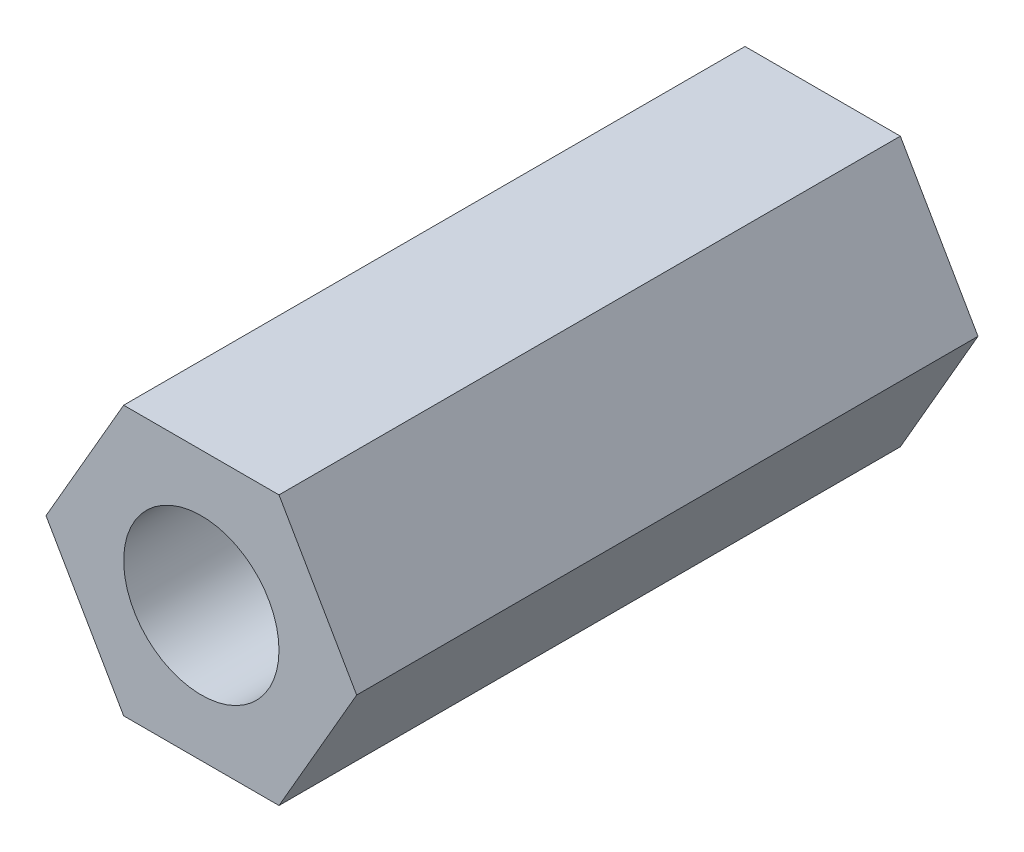
SolidWorks part; units mm, degrees
material "普通碳钢"
ref_plane "前视" through (0, 0, 0) normal (0, 0, 1) x (1, 0, 0)
ref_plane "上视" through (0, 0, 0) normal (0, 1, 0) x (1, 0, 0)
ref_plane "右视" through (0, 0, 0) normal (1, 0, 0) x (0, 0, -1)
sketch "草图1" plane through (0, 0, 0) normal (0, 0, 1) x (1, 0, 0)
  line L0 (0, 0) -> (2.5, 0)
  line L1 (2.5, 0) -> (3.75, -2.1651)
  line L2 (3.75, -2.1651) -> (2.5, -4.3301)
  line L3 (2.5, -4.3301) -> (0, -4.3301)
  line L4 (0, -4.3301) -> (-1.25, -2.1651)
  line L5 (-1.25, -2.1651) -> (0, 0)
  dimension "D1" = 5
  dimension "D2" = 5
extrude "凸台-拉伸1" add sketch "草图1" along normal blind 10
hole_wizard "M3 螺纹孔1" positions "草图3" profile "草图2" tap size "M3" standard "GB" end condition through all
sketch "草图3" plane through (0, 0, 10) normal (0, 0, 1) x (1, 0, 0)
  line L0 (-1.25, -2.1651) -> (3.75, -2.1651) construction
  line L2 (1.25, 0) -> (1.25, -4.3301) construction
  line L3 (2.5, 0) -> (0, 0) construction
  line L4 (0, -4.3301) -> (2.5, -4.3301) construction
  point P0 (1.25, -2.1651)
cosmetic thread "孔螺蚊线1" parameters "D2"=3
sketch "草图2" plane through (1.25, -2.1651, 10) normal (1, 0, 0) x (0, -1, 0)
  line L0 (0, 0) -> (0, 10)
  line L1 (0, 10) -> (1.25, 10)
  line L2 (1.25, 10) -> (1.25, 0)
  line L5 (1.25, 0) -> (0, 0)
  line L11 (0, -6.35) -> (0, 107.95) construction
  dimension "通孔螺纹孔钻头直径" = 2.5
  dimension "通孔螺纹孔钻头深度" = 10
